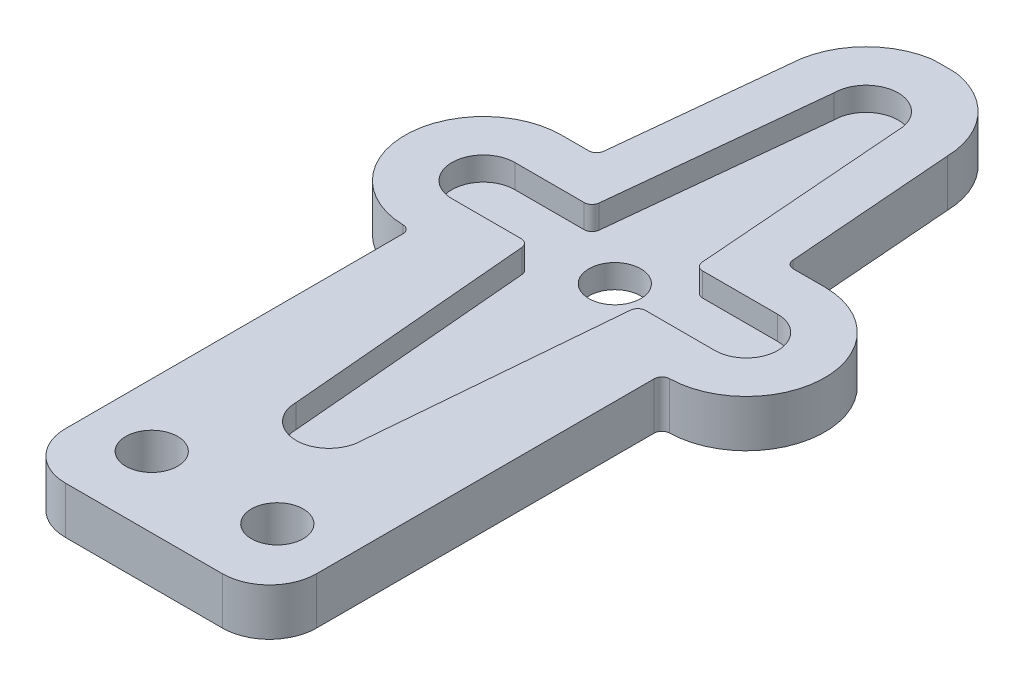
SolidWorks part; units mm, degrees
ref_plane "Plano frontal" through (0, 0, 0) normal (0, 0, 1) x (1, 0, 0)
ref_plane "Plano superior" through (0, 0, 0) normal (0, 1, 0) x (1, 0, 0)
ref_plane "Plano direito" through (0, 0, 0) normal (1, 0, 0) x (0, 0, -1)
sketch "Sketch1" plane through (0, 0, 0) normal (0, 1, 0) x (1, 0, 0)
  circle A0 centre (0, 0) radius 21
  dimension "D1" = 42
extrude "Boss-Extrude1" add sketch "Sketch1" along normal mid plane 3
sketch "Sketch5" plane through (0, 0, 0) normal (0, 1, 0) x (1, 0, 0)
  line L1 (-8, 0) -> (8, 0)
  line L2 (-8, 0) -> (-8, -30)
  line L3 (-8, -30) -> (8, -30)
  line L4 (8, 0) -> (8, -30)
  point P4 (0, 0)
  dimension "D1" = 16
  dimension "D2" = 30
extrude "Boss-Extrude2" add sketch "Sketch5" along normal mid plane 3
sketch "Sketch2" plane through (0, 1.5, 0) normal (0, 1, 0) x (1, 0, 0)
  line L0 (2.1, -18.2) -> (3.5, -2)
  line L1 (-2.1, -18.2) -> (-3.5, -2)
  line L2 (-21, 0) -> (21, 0)
  line L3 (2.05, 16) -> (3.13, 2)
  line L4 (-8.375, -2) -> (8.375, -2)
  line L5 (-8.375, -2) -> (-8.375, 2)
  line L6 (-8.375, 2) -> (8.375, 2)
  line L7 (8.375, -2) -> (8.375, 2)
  line L8 (-8.375, -2) -> (8.375, 2) construction
  line L9 (-8.375, 2) -> (8.375, -2) construction
  line L10 (-2.05, 16) -> (-3.5, 2)
  circle A0 centre (0, 0) radius 3.65
  circle A1 centre (0, -18.2) radius 2.1
  circle A2 centre (0, 0) radius 21 construction
  circle A3 centre (-8.375, 0) radius 2
  circle A4 centre (8.375, 0) radius 2
  circle A5 centre (0, 16) radius 2.05
  dimension "D1" = 7.3
  dimension "D2" = 4.2
  dimension "D6" = 4
  dimension "D7" = 4
  dimension "D9" = 4.1
  dimension "D8" = 16.75
  dimension "D4" = 3.5
  dimension "D5" = 3.5
  dimension "D10" = 3.13
  dimension "D11" = 3.5
  dimension "D3" = 20.2
  dimension "D12" = 18
extrude "Cut-Extrude1" cut sketch "Sketch2" against normal blind 1.5
sketch "Sketch4" plane through (0, 0, 0) normal (0, 1, 0) x (1, 0, 0)
  circle A0 centre (0, 0) radius 1.65
  dimension "D1" = 3.3
extrude "Cut-Extrude4" cut sketch "Sketch4" against normal up to next
sketch "Sketch6" plane through (0, 1.5, 0) normal (0, 1, 0) x (1, 0, 0)
  line L0 (-8, -30) -> (8, -30) construction
  circle A0 centre (4, -25.5) radius 1.65
  circle A1 centre (-4, -25.5) radius 1.65
  dimension "D1" = 3.3
  dimension "D2" = 3.3
  dimension "D3" = 4.5
  dimension "D4" = 4
  dimension "D5" = 4
extrude "Cut-Extrude5" cut sketch "Sketch6" against normal up to next
sketch "Sketch7" plane through (0, 0, 0) normal (0, 1, 0) x (1, 0, 0)
  line L0 (-8, -19.4165) -> (-8, -5)
  line L1 (8, -19.4165) -> (8, -5)
  line L4 (-8, -19.4165) -> (-8, -30)
  line L9 (6.2519, -5) -> (8.375, -5)
  line L11 (6.2519, -5) -> (8.375, -5)
  line L13 (-8, -19.4165) -> (-8, -30)
  line L16 (8.375, 5) -> (5.9075, 5)
  line L33 (8.375, 5) -> (5.9075, 5)
  line L35 (-8, -30) -> (8, -30)
  line L36 (-8, -30) -> (8, -30)
  line L37 (8, -30) -> (8, -19.4165)
  line L38 (8, -30) -> (8, -19.4165)
  line L39 (5.9075, 5) -> (5.048, 16.1411)
  line L40 (5.9075, 5) -> (5.048, 16.1411)
  line L41 (-5.0465, 16.1892) -> (-6.2053, 5)
  line L42 (-5.0465, 16.1892) -> (-6.2053, 5)
  line L43 (-6.2053, 5) -> (-8.375, 5)
  line L44 (-6.2053, 5) -> (-8.375, 5)
  line L45 (-8.375, -5) -> (-6.2519, -5)
  line L46 (-8.375, -5) -> (-6.2519, -5)
  line L47 (-6.2519, -5) -> (-5.0976, -18.3576)
  line L48 (-6.2519, -5) -> (-5.0976, -18.3576)
  line L49 (5.0976, -18.3576) -> (6.2519, -5)
  line L50 (5.0976, -18.3576) -> (6.2519, -5)
  arc A2 (-5.0976, -18.3576) -> (5.0976, -18.3576) centre (0, -18.2) ccw
  arc A3 (8, -19.4165) -> (-8, -19.4165) centre (0, 0) ccw
  arc A4 (-5.0976, -18.3576) -> (5.0976, -18.3576) centre (0, -18.2) ccw
  arc A10 (8, -19.4165) -> (-8, -19.4165) centre (0, 0) ccw
  arc A11 (8.375, -5) -> (8.375, 5) centre (8.375, 0) ccw
  arc A17 (8.375, -5) -> (8.375, 5) centre (8.375, 0) ccw
  arc A19 (5.048, 16.1411) -> (-5.0465, 16.1892) centre (0, 16) ccw
  arc A20 (5.048, 16.1411) -> (-5.0465, 16.1892) centre (0, 16) ccw
  arc A21 (-8.375, 5) -> (-8.375, -5) centre (-8.375, 0) ccw
  arc A22 (-8.375, 5) -> (-8.375, -5) centre (-8.375, 0) ccw
  dimension "D1" = 3
  dimension "D2" = 0
extrude "Cut-Extrude6" cut sketch "Sketch7" against normal through all and the other way through all contours A22 L44 L42 A20 A10 L0 L46 | A20 L40 L33 A17 L11 L1 A10
fillet "Fillet3" radius 0.5 8 edges at (-8, 0, 5) (8, 0, 5) (-3.5, 0.75, -2) (3.5, 0.75, 2) (3.13, 0.75, -2) (-3.5, 0.75, 2) (-6.2053, 0, -5) (5.9075, 0, -5)
fillet "Fillet4" radius 3 2 edges at (-8, 0, 30) (8, 0, 30)
equation "\"D2@Sketch6\"=\"D1@Sketch6\""
equation "\"D5@Sketch6\"=\"D4@Sketch6\""
equation "\"D7@Sketch2\"=\"D6@Sketch2\""
equation "\"D5@Sketch2\"=\"D4@Sketch2\""
equation "\"D11@Sketch2\"=\"D4@Sketch2\""
